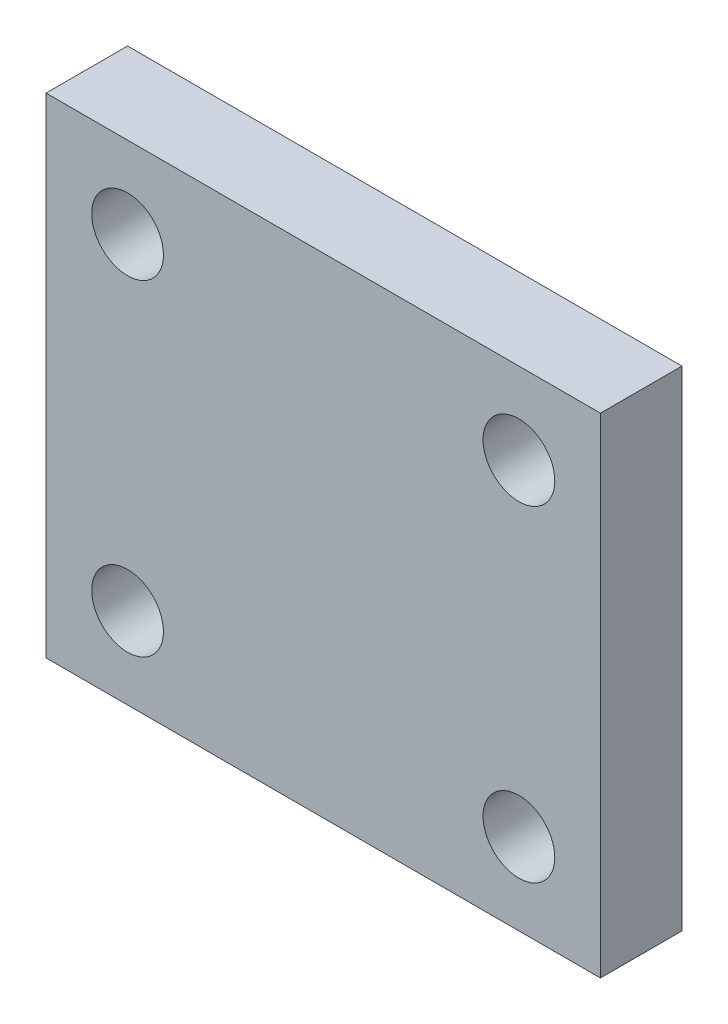
SolidWorks part; units mm, degrees
ref_plane "前视基准面" through (0, 0, 0) normal (0, 0, 1) x (1, 0, 0)
ref_plane "上视基准面" through (0, 0, 0) normal (0, 1, 0) x (1, 0, 0)
ref_plane "右视基准面" through (0, 0, 0) normal (1, 0, 0) x (0, 0, -1)
sketch "草图2" plane through (0, 0, 0) normal (0, 0, 1) x (1, 0, 0)
  line L1 (-17, 15) -> (17, 15)
  line L2 (-17, 15) -> (-17, -15)
  line L3 (-17, -15) -> (17, -15)
  line L4 (17, 15) -> (17, -15)
  line L5 (-17, 15) -> (17, -15) construction
  line L6 (-17, -15) -> (17, 15) construction
  point P0 (0, 0)
  dimension "D1" = 34
  dimension "D2" = 30
extrude "凸台-拉伸1" add sketch "草图2" along normal blind 5
sketch "草图3" plane through (0, 0, 5) normal (0, 0, 1) x (1, 0, 0)
  line L1 (-12, 10) -> (12, 10)
  line L2 (-12, 10) -> (-12, -10)
  line L3 (-12, -10) -> (12, -10)
  line L4 (12, 10) -> (12, -10)
  line L5 (-12, 10) -> (12, -10) construction
  line L6 (-12, -10) -> (12, 10) construction
  point P0 (0, 0)
  dimension "D1" = 24
  dimension "D2" = 20
sketch "草图4" plane through (0, 0, 5) normal (0, 0, 1) x (1, 0, 0)
  point P0 (-12, 10)
  point P3 (12, 10)
  point P6 (12, -10)
  point P9 (-12, -10)
hole_wizard "孔1" positions "草图4" profile "草图5" legacy end condition up to next
sketch "草图5" plane through (-12, 10, 5) normal (1, 0, 0) x (0, -1, 0)
  line L0 (0, 0) -> (0, 5)
  line L1 (0, 5) -> (2.2, 5)
  line L2 (2.2, 5) -> (2.2, 0)
  line L3 (2.2, 0) -> (0, 0)
  line L4 (0, 110) -> (0, -10) construction
  dimension "直径" = 4.4
  dimension "深度" = 5
